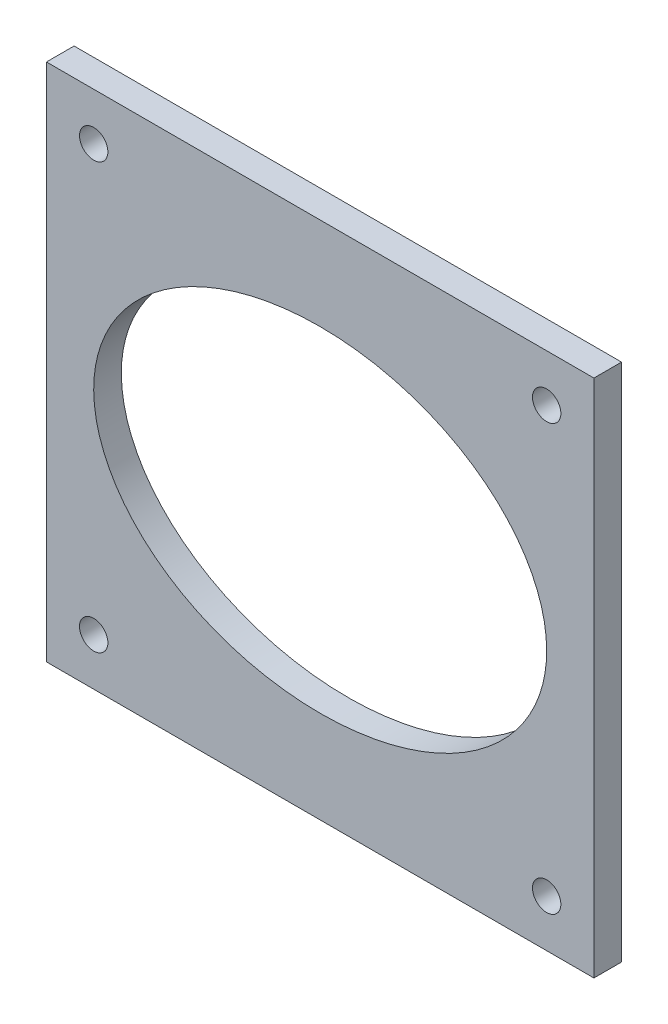
SolidWorks part; units mm, degrees
ref_plane "Front Plane" through (0, 0, 0) normal (0, 0, 1) x (1, 0, 0)
ref_plane "Top Plane" through (0, 0, 0) normal (0, 1, 0) x (1, 0, 0)
ref_plane "Right Plane" through (0, 0, 0) normal (1, 0, 0) x (0, 0, -1)
sketch "Sketch1" plane through (0, 0, 0) normal (0, 0, 1) x (1, 0, 0)
  line L0 (-47.95, 45) -> (47.95, 45) construction
  line L1 (57.95, -55) -> (-57.95, -55)
  line L2 (57.95, -55) -> (57.95, 55)
  line L3 (57.95, 55) -> (-57.95, 55)
  line L4 (-57.95, -55) -> (-57.95, 55)
  line L5 (57.95, -55) -> (-57.95, 55) construction
  line L6 (57.95, 55) -> (-57.95, -55) construction
  line L7 (0, 0) -> (65.7887, 0) construction
  line L8 (-47.95, -45) -> (47.95, -45) construction
  line L9 (-47.95, 45) -> (-47.95, -45) construction
  line L10 (0, 0) -> (0, 81.9674) construction
  circle A0 centre (-47.95, 45) radius 3
  circle A1 centre (-47.95, -45) radius 3
  circle A2 centre (47.95, -45) radius 3
  circle A3 centre (47.95, 45) radius 3
  ellipse E0 centre (0, 0) end of major axis (47.95, 0) minor radius 35.45
  point P18 (0, 0)
  point P21 (0, 0)
  dimension "D2" = 6
  dimension "D1" = 90
  dimension "D4" = 10
  dimension "D7" = 10
  dimension "D5" = 10
  dimension "D6" = 10
  dimension "D8" = 95.9
  dimension "D9" = 70.9
extrude "Boss-Extrude1" add sketch "Sketch1" along normal blind 5.85
equation "\"D5@Sketch1\"=\"D4@Sketch1\""
equation "\"D6@Sketch1\"=\"D7@Sketch1\""
